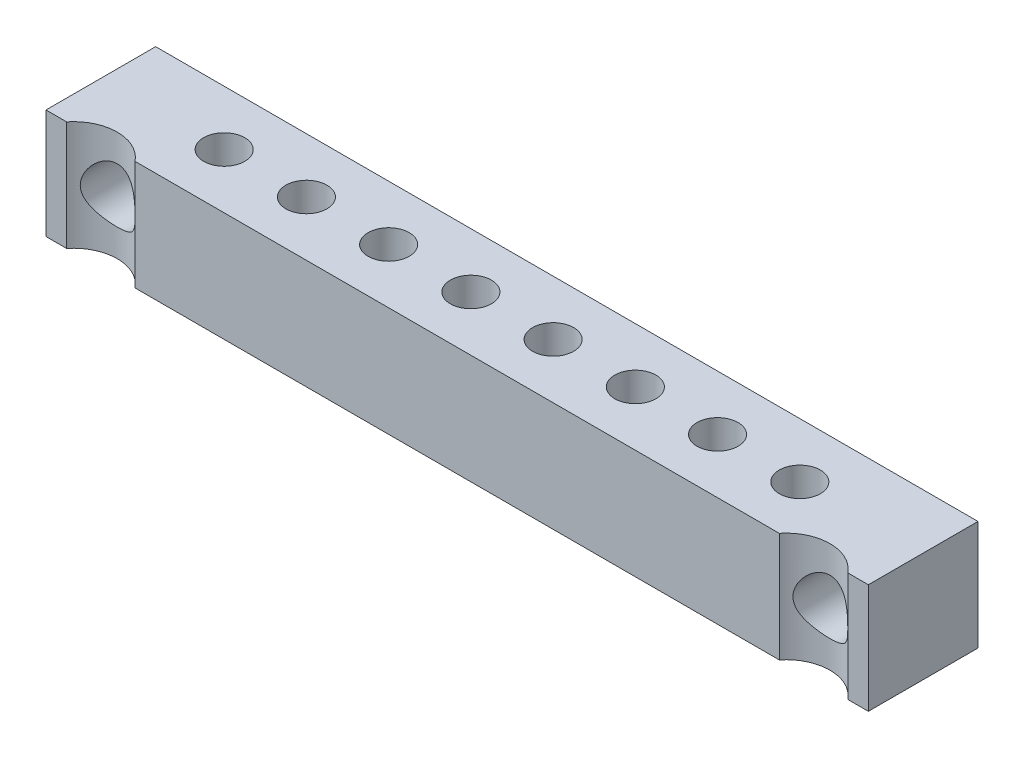
SolidWorks part; units mm, degrees
material "Aleación 1060"
ref_plane "Alzado" through (0, 0, 0) normal (0, 0, 1) x (1, 0, 0)
ref_plane "Planta" through (0, 0, 0) normal (0, 1, 0) x (1, 0, 0)
ref_plane "Vista lateral" through (0, 0, 0) normal (1, 0, 0) x (0, 0, -1)
sketch "Croquis1" plane through (0, 0, 0) normal (0, 0, 1) x (1, 0, 0)
  line L0 (15, 4) -> (15, 0) construction
  line L1 (0, 0) -> (30, 0)
  line L2 (0, 0) -> (0, 4)
  line L3 (0, 4) -> (30, 4)
  line L4 (30, 0) -> (30, 4)
  circle A0 centre (2, 2) radius 1
  circle A1 centre (28, 2) radius 1
  dimension "D3" = 2
  dimension "D5" = 2
  dimension "D1" = 30
  dimension "D2" = 4
  dimension "D4" = 2
extrude "Saliente-Extruir1" add sketch "Croquis1" along normal blind 4
sketch "Croquis2" plane through (0, 0, 0) normal (0, -1, 0) x (1, 0, 0)
  line L0 (0, 4) -> (30, 4) construction
  line L1 (15, 4) -> (15, 0) construction
  line L2 (0, 0) -> (30, 0) construction
  line L3 (10.5, 2) -> (13.5, 2) construction
  circle A0 centre (2, 5) radius 1.6
  circle A1 centre (13.5, 2) radius 0.75
  circle A2 centre (10.5, 2) radius 0.75
  circle A3 centre (7.5, 2) radius 0.75
  circle A4 centre (22.5, 2) radius 0.75
  circle A5 centre (19.5, 2) radius 0.75
  circle A6 centre (16.5, 2) radius 0.75
  circle A7 centre (28, 5) radius 1.6
  circle A8 centre (25.5, 2) radius 0.75
  circle A9 centre (4.5, 2) radius 0.75
  dimension "D1" = 1
  dimension "D2" = 2
  dimension "D3" = 1.5
  dimension "D4" = 1.5
  dimension "D6" = 2
  dimension "D5" = 3
  dimension "D7" = 2
extrude "Cortar-Extruir1" cut sketch "Croquis2" against normal up to vertex (4 mm away)
